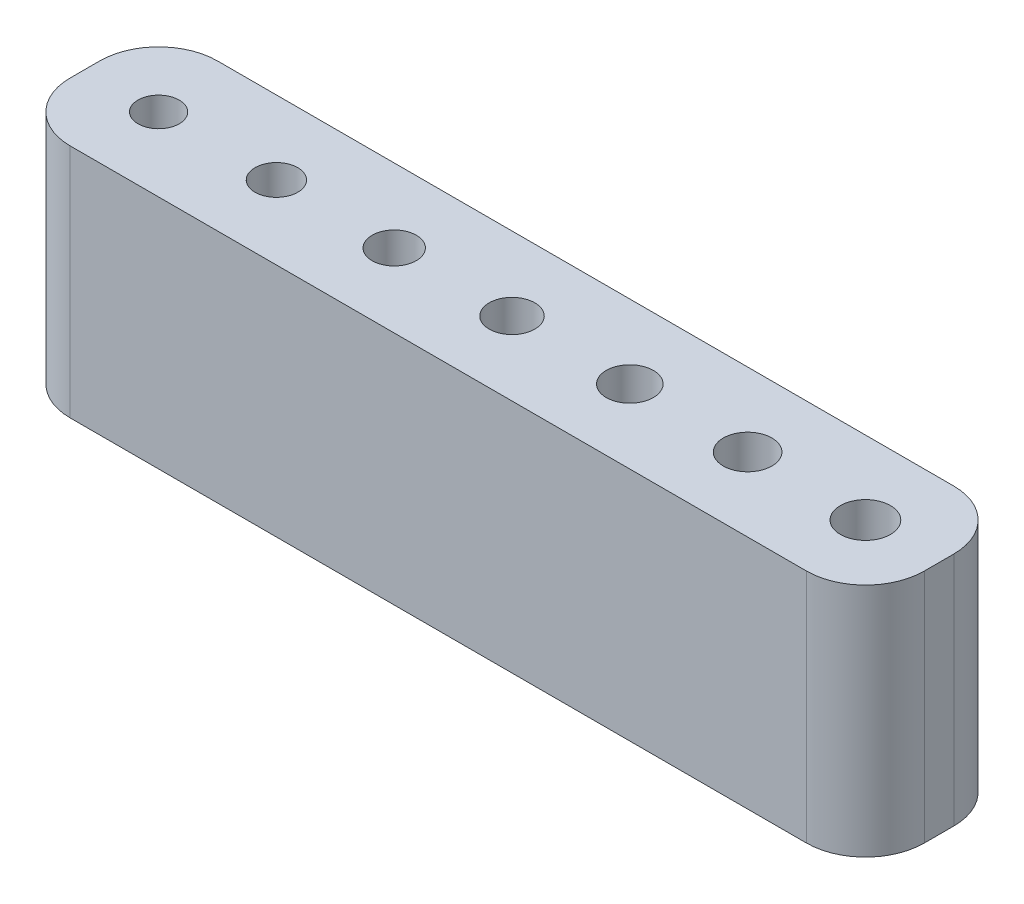
SolidWorks part; units mm, degrees
ref_plane "Front Plane" through (0, 0, 0) normal (0, 0, 1) x (1, 0, 0)
ref_plane "Top Plane" through (0, 0, 0) normal (0, 1, 0) x (1, 0, 0)
ref_plane "Right Plane" through (0, 0, 0) normal (1, 0, 0) x (0, 0, -1)
sketch "Sketch1" plane through (0, 0, 0) normal (0, 1, 0) x (1, 0, 0)
  line L0 (2.5, 2.5) -> (26.5, 2.5) construction
  line L1 (0, 0) -> (29, 0)
  line L2 (0, 0) -> (0, 5)
  line L3 (0, 5) -> (29, 5)
  line L4 (29, 0) -> (29, 5)
  circle A0 centre (2.5, 2.5) radius 0.7
  circle A1 centre (6.5, 2.5) radius 0.725
  circle A2 centre (10.5, 2.5) radius 0.75
  circle A3 centre (14.5, 2.5) radius 0.775
  circle A4 centre (26.5, 2.5) radius 0.85
  circle A10 centre (18.5, 2.5) radius 0.8
  circle A11 centre (22.5, 2.5) radius 0.825
  dimension "D1" = 1.4
  dimension "D2" = 1.45
  dimension "D3" = 1.5
  dimension "D4" = 1.55
  dimension "D5" = 1.7
  dimension "D6" = 4
  dimension "D7" = 4
  dimension "D8" = 4
  dimension "D9" = 1.6
  dimension "D10" = 1.65
  dimension "D13" = 4
  dimension "D14" = 4
  dimension "D15" = 4
  dimension "D16" = 2.5
  dimension "D18" = 2.5
  dimension "D11" = 2.5
  dimension "D12" = 2.5
  dimension "D17" = 2.5
extrude "Boss-Extrude1" add sketch "Sketch1" along normal blind 8
fillet "Fillet1" radius 2 4 edges at (0, 4, -5) (29, 4, -5) (0, 4, 0) (29, 4, 0)
